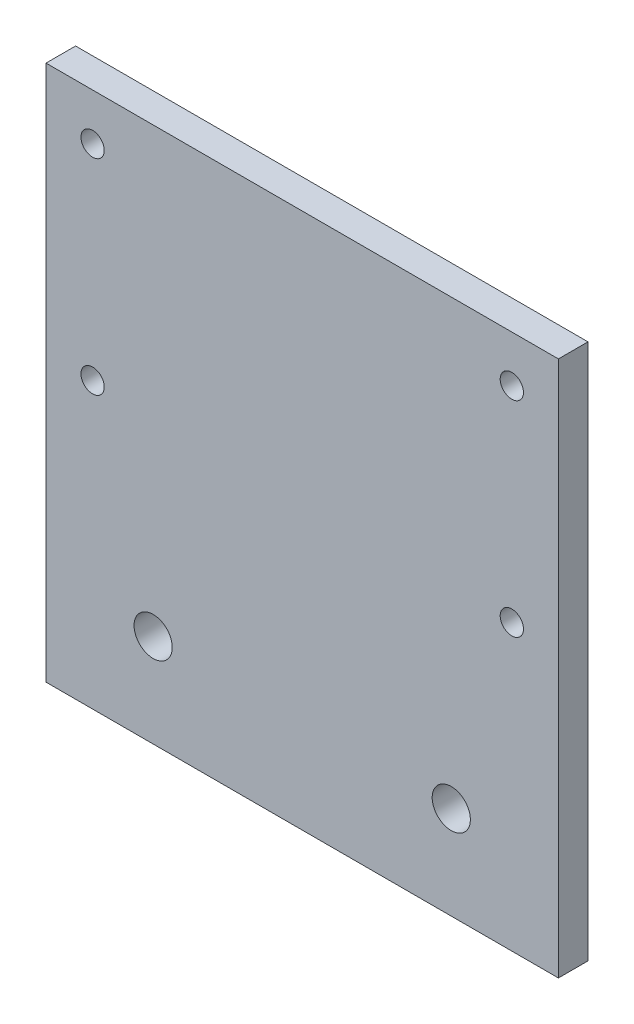
SolidWorks part; units mm, degrees
ref_plane "Front Plane" through (0, 0, 0) normal (0, 0, 1) x (1, 0, 0)
ref_plane "Top Plane" through (0, 0, 0) normal (0, 1, 0) x (1, 0, 0)
ref_plane "Right Plane" through (0, 0, 0) normal (1, 0, 0) x (0, 0, -1)
sketch "Sketch1" plane through (0, 0, 0) normal (0, 0, 1) x (1, 0, 0)
  line L0 (27.5, 57.55) -> (27.5, 0) construction
  line L1 (0, 0) -> (55, 0)
  line L2 (0, 0) -> (0, 57.55)
  line L3 (0, 57.55) -> (55, 57.55)
  line L4 (55, 0) -> (55, 57.55)
  line L5 (5, 52.55) -> (50, 52.55) construction
  line L6 (5, 52.55) -> (5, 30.55) construction
  line L7 (5, 30.55) -> (50, 30.55) construction
  line L8 (50, 52.55) -> (50, 30.55) construction
  line L9 (11.5, 10) -> (43.5, 10) construction
  circle A0 centre (5, 52.55) radius 1.25
  circle A1 centre (50, 52.55) radius 1.25
  circle A2 centre (50, 30.55) radius 1.25
  circle A3 centre (5, 30.55) radius 1.25
  circle A4 centre (11.5, 10) radius 2.05
  circle A5 centre (43.5, 10) radius 2.05
  point P11 (27.5, 52.55)
  point P23 (27.5, 10)
  dimension "D6" = 2.5
  dimension "D9" = 4.1
  dimension "D10" = 4.1
  dimension "D1" = 55
  dimension "D2" = 57.55
  dimension "D3" = 45
  dimension "D4" = 22
  dimension "D5" = 5
  dimension "D11" = 32
  dimension "D12" = 20
  dimension "D7" = 2
  dimension "D8" = 2
extrude "Boss-Extrude1" add sketch "Sketch1" along normal blind 3.175
